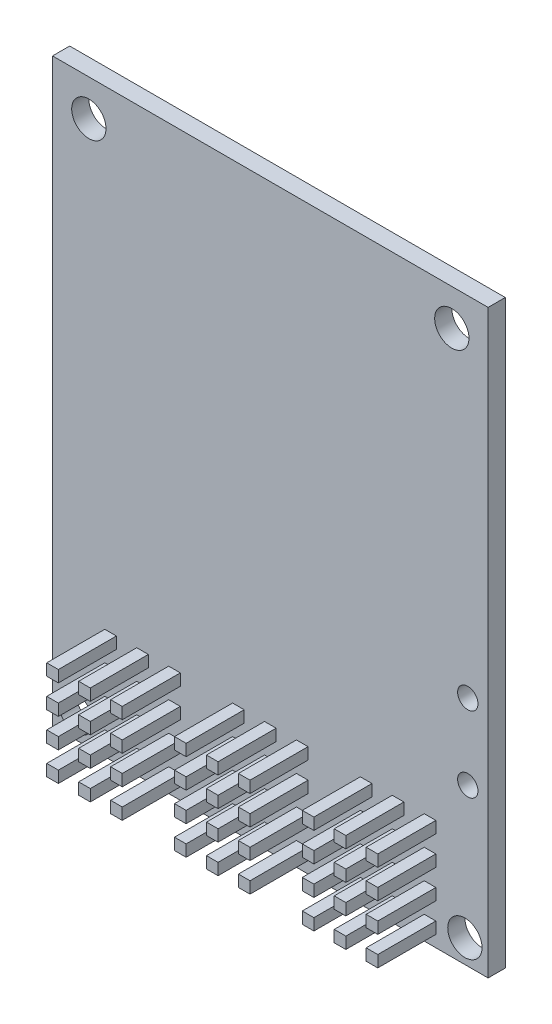
SolidWorks part; units mm, degrees
ref_plane "Front Plane" through (0, 0, 0) normal (0, 0, 1) x (1, 0, 0)
ref_plane "Top Plane" through (0, 0, 0) normal (0, 1, 0) x (1, 0, 0)
ref_plane "Right Plane" through (0, 0, 0) normal (1, 0, 0) x (0, 0, -1)
sketch "Sketch1" plane through (0, 0, 0) normal (0, 0, 1) x (1, 0, 0)
  line L0 (0, 25.4) -> (0, -25.4) construction
  line L1 (19.05, -25.4) -> (-19.05, -25.4)
  line L2 (19.05, -25.4) -> (19.05, 25.4)
  line L3 (19.05, 25.4) -> (-19.05, 25.4)
  line L4 (-19.05, -25.4) -> (-19.05, 25.4)
  line L5 (19.05, -25.4) -> (-19.05, 25.4) construction
  line L6 (19.05, 25.4) -> (-19.05, -25.4) construction
  circle A0 centre (-17.018, -23.368) radius 1.5
  circle A1 centre (-15.875, 22.225) radius 1.5
  circle A2 centre (17.018, -23.368) radius 1.5
  circle A3 centre (15.875, 22.225) radius 1.5
  point P0 (0, 0)
  dimension "D5" = 3
  dimension "D1" = 38.1
  dimension "D2" = 50.8
  dimension "D3" = 2.032
  dimension "D4" = 2.032
  dimension "D6" = 3.175
  dimension "D7" = 3.175
extrude "Boss-Extrude1" add sketch "Sketch1" along normal blind 1.5
sketch "Sketch2" plane through (0, 0, 1.5) normal (0, 0, 1) x (1, 0, 0)
  line L0 (19.05, -25.4) -> (19.05, 25.4) construction
  line L1 (-19.05, -25.4) -> (19.05, -25.4) construction
  circle A0 centre (17.272, -11.684) radius 0.889
  circle A1 centre (17.272, -5.08) radius 0.889
  dimension "D3" = 1.778
  dimension "D1" = 1.778
  dimension "D2" = 13.716
  dimension "D4" = 6.604
  dimension "D5" = 1.778
extrude "Cut-Extrude1" cut sketch "Sketch2" against normal through all
sketch "Sketch3" plane through (0, 0, 1.5) normal (0, 0, 1) x (1, 0, 0)
  line L0 (-19.05, -23.876) -> (-13.97, -23.876) construction
  line L1 (-19.05, 25.4) -> (-19.05, -25.4) construction
  line L2 (-19.05, -25.4) -> (19.05, -25.4) construction
  line L3 (-13.462, -24.384) -> (-14.478, -24.384)
  line L4 (-13.462, -24.384) -> (-13.462, -23.368)
  line L5 (-13.462, -23.368) -> (-14.478, -23.368)
  line L6 (-14.478, -24.384) -> (-14.478, -23.368)
  line L7 (-13.462, -24.384) -> (-14.478, -23.368) construction
  line L8 (-13.462, -23.368) -> (-14.478, -24.384) construction
  line L9 (-13.462, -20.828) -> (-14.478, -20.828)
  line L10 (-13.462, -21.844) -> (-13.462, -20.828)
  line L11 (-13.462, -21.844) -> (-14.478, -21.844)
  line L12 (-14.478, -21.844) -> (-14.478, -20.828)
  line L13 (-13.462, -18.288) -> (-14.478, -18.288)
  line L14 (-13.462, -19.304) -> (-13.462, -18.288)
  line L15 (-13.462, -19.304) -> (-14.478, -19.304)
  line L16 (-14.478, -19.304) -> (-14.478, -18.288)
  line L17 (-13.462, -15.748) -> (-14.478, -15.748)
  line L18 (-13.462, -16.764) -> (-13.462, -15.748)
  line L19 (-13.462, -16.764) -> (-14.478, -16.764)
  line L20 (-14.478, -16.764) -> (-14.478, -15.748)
  line L21 (-10.668, -23.368) -> (-11.684, -23.368)
  line L22 (-10.668, -24.384) -> (-10.668, -23.368)
  line L23 (-10.668, -24.384) -> (-11.684, -24.384)
  line L24 (-11.684, -24.384) -> (-11.684, -23.368)
  line L25 (-10.668, -20.828) -> (-11.684, -20.828)
  line L26 (-10.668, -21.844) -> (-10.668, -20.828)
  line L27 (-10.668, -21.844) -> (-11.684, -21.844)
  line L28 (-11.684, -21.844) -> (-11.684, -20.828)
  line L29 (-10.668, -18.288) -> (-11.684, -18.288)
  line L30 (-10.668, -19.304) -> (-10.668, -18.288)
  line L31 (-10.668, -19.304) -> (-11.684, -19.304)
  line L32 (-11.684, -19.304) -> (-11.684, -18.288)
  line L33 (-10.668, -15.748) -> (-11.684, -15.748)
  line L34 (-10.668, -16.764) -> (-10.668, -15.748)
  line L35 (-10.668, -16.764) -> (-11.684, -16.764)
  line L36 (-11.684, -16.764) -> (-11.684, -15.748)
  line L37 (-7.874, -23.368) -> (-8.89, -23.368)
  line L38 (-7.874, -24.384) -> (-7.874, -23.368)
  line L39 (-7.874, -24.384) -> (-8.89, -24.384)
  line L40 (-8.89, -24.384) -> (-8.89, -23.368)
  line L41 (-7.874, -20.828) -> (-8.89, -20.828)
  line L42 (-7.874, -21.844) -> (-7.874, -20.828)
  line L43 (-7.874, -21.844) -> (-8.89, -21.844)
  line L44 (-8.89, -21.844) -> (-8.89, -20.828)
  line L45 (-7.874, -18.288) -> (-8.89, -18.288)
  line L46 (-7.874, -19.304) -> (-7.874, -18.288)
  line L47 (-7.874, -19.304) -> (-8.89, -19.304)
  line L48 (-8.89, -19.304) -> (-8.89, -18.288)
  line L49 (-7.874, -15.748) -> (-8.89, -15.748)
  line L50 (-7.874, -16.764) -> (-7.874, -15.748)
  line L51 (-7.874, -16.764) -> (-8.89, -16.764)
  line L52 (-8.89, -16.764) -> (-8.89, -15.748)
  line L53 (-2.286, -23.368) -> (-3.302, -23.368)
  line L54 (-2.286, -24.384) -> (-2.286, -23.368)
  line L55 (-2.286, -24.384) -> (-3.302, -24.384)
  line L56 (-3.302, -24.384) -> (-3.302, -23.368)
  line L57 (-2.286, -20.828) -> (-3.302, -20.828)
  line L58 (-2.286, -21.844) -> (-2.286, -20.828)
  line L59 (-2.286, -21.844) -> (-3.302, -21.844)
  line L60 (-3.302, -21.844) -> (-3.302, -20.828)
  line L61 (-2.286, -18.288) -> (-3.302, -18.288)
  line L62 (-2.286, -19.304) -> (-2.286, -18.288)
  line L63 (-2.286, -19.304) -> (-3.302, -19.304)
  line L64 (-3.302, -19.304) -> (-3.302, -18.288)
  line L65 (-2.286, -15.748) -> (-3.302, -15.748)
  line L66 (-2.286, -16.764) -> (-2.286, -15.748)
  line L67 (-2.286, -16.764) -> (-3.302, -16.764)
  line L68 (-3.302, -16.764) -> (-3.302, -15.748)
  line L69 (0.508, -23.368) -> (-0.508, -23.368)
  line L70 (0.508, -24.384) -> (0.508, -23.368)
  line L71 (0.508, -24.384) -> (-0.508, -24.384)
  line L72 (-0.508, -24.384) -> (-0.508, -23.368)
  line L73 (0.508, -20.828) -> (-0.508, -20.828)
  line L74 (0.508, -21.844) -> (0.508, -20.828)
  line L75 (0.508, -21.844) -> (-0.508, -21.844)
  line L76 (-0.508, -21.844) -> (-0.508, -20.828)
  line L77 (0.508, -18.288) -> (-0.508, -18.288)
  line L78 (0.508, -19.304) -> (0.508, -18.288)
  line L79 (0.508, -19.304) -> (-0.508, -19.304)
  line L80 (-0.508, -19.304) -> (-0.508, -18.288)
  line L81 (0.508, -15.748) -> (-0.508, -15.748)
  line L82 (0.508, -16.764) -> (0.508, -15.748)
  line L83 (0.508, -16.764) -> (-0.508, -16.764)
  line L84 (-0.508, -16.764) -> (-0.508, -15.748)
  line L85 (3.302, -23.368) -> (2.286, -23.368)
  line L86 (3.302, -24.384) -> (3.302, -23.368)
  line L87 (3.302, -24.384) -> (2.286, -24.384)
  line L88 (2.286, -24.384) -> (2.286, -23.368)
  line L89 (3.302, -20.828) -> (2.286, -20.828)
  line L90 (3.302, -21.844) -> (3.302, -20.828)
  line L91 (3.302, -21.844) -> (2.286, -21.844)
  line L92 (2.286, -21.844) -> (2.286, -20.828)
  line L93 (3.302, -18.288) -> (2.286, -18.288)
  line L94 (3.302, -19.304) -> (3.302, -18.288)
  line L95 (3.302, -19.304) -> (2.286, -19.304)
  line L96 (2.286, -19.304) -> (2.286, -18.288)
  line L97 (3.302, -15.748) -> (2.286, -15.748)
  line L98 (3.302, -16.764) -> (3.302, -15.748)
  line L99 (3.302, -16.764) -> (2.286, -16.764)
  line L100 (2.286, -16.764) -> (2.286, -15.748)
  line L101 (8.89, -23.368) -> (7.874, -23.368)
  line L102 (8.89, -24.384) -> (8.89, -23.368)
  line L103 (8.89, -24.384) -> (7.874, -24.384)
  line L104 (7.874, -24.384) -> (7.874, -23.368)
  line L105 (8.89, -20.828) -> (7.874, -20.828)
  line L106 (8.89, -21.844) -> (8.89, -20.828)
  line L107 (8.89, -21.844) -> (7.874, -21.844)
  line L108 (7.874, -21.844) -> (7.874, -20.828)
  line L109 (8.89, -18.288) -> (7.874, -18.288)
  line L110 (8.89, -19.304) -> (8.89, -18.288)
  line L111 (8.89, -19.304) -> (7.874, -19.304)
  line L112 (7.874, -19.304) -> (7.874, -18.288)
  line L113 (8.89, -15.748) -> (7.874, -15.748)
  line L114 (8.89, -16.764) -> (8.89, -15.748)
  line L115 (8.89, -16.764) -> (7.874, -16.764)
  line L116 (7.874, -16.764) -> (7.874, -15.748)
  line L117 (11.684, -23.368) -> (10.668, -23.368)
  line L118 (11.684, -24.384) -> (11.684, -23.368)
  line L119 (11.684, -24.384) -> (10.668, -24.384)
  line L120 (10.668, -24.384) -> (10.668, -23.368)
  line L121 (11.684, -20.828) -> (10.668, -20.828)
  line L122 (11.684, -21.844) -> (11.684, -20.828)
  line L123 (11.684, -21.844) -> (10.668, -21.844)
  line L124 (10.668, -21.844) -> (10.668, -20.828)
  line L125 (11.684, -18.288) -> (10.668, -18.288)
  line L126 (11.684, -19.304) -> (11.684, -18.288)
  line L127 (11.684, -19.304) -> (10.668, -19.304)
  line L128 (10.668, -19.304) -> (10.668, -18.288)
  line L129 (11.684, -15.748) -> (10.668, -15.748)
  line L130 (11.684, -16.764) -> (11.684, -15.748)
  line L131 (11.684, -16.764) -> (10.668, -16.764)
  line L132 (10.668, -16.764) -> (10.668, -15.748)
  line L133 (14.478, -23.368) -> (13.462, -23.368)
  line L134 (14.478, -24.384) -> (14.478, -23.368)
  line L135 (14.478, -24.384) -> (13.462, -24.384)
  line L136 (13.462, -24.384) -> (13.462, -23.368)
  line L137 (14.478, -20.828) -> (13.462, -20.828)
  line L138 (14.478, -21.844) -> (14.478, -20.828)
  line L139 (14.478, -21.844) -> (13.462, -21.844)
  line L140 (13.462, -21.844) -> (13.462, -20.828)
  line L141 (14.478, -18.288) -> (13.462, -18.288)
  line L142 (14.478, -19.304) -> (14.478, -18.288)
  line L143 (14.478, -19.304) -> (13.462, -19.304)
  line L144 (13.462, -19.304) -> (13.462, -18.288)
  line L145 (14.478, -15.748) -> (13.462, -15.748)
  line L146 (14.478, -16.764) -> (14.478, -15.748)
  line L147 (14.478, -16.764) -> (13.462, -16.764)
  line L148 (13.462, -16.764) -> (13.462, -15.748)
  dimension "D1" = 5.08
  dimension "D2" = 1.016
  dimension "D3" = 1.016
  dimension "D4" = 1.524
  dimension "D5" = 4
  dimension "D6" = 3
  dimension "D7" = 3
extrude "Boss-Extrude2" add sketch "Sketch3" along normal blind 5.08
